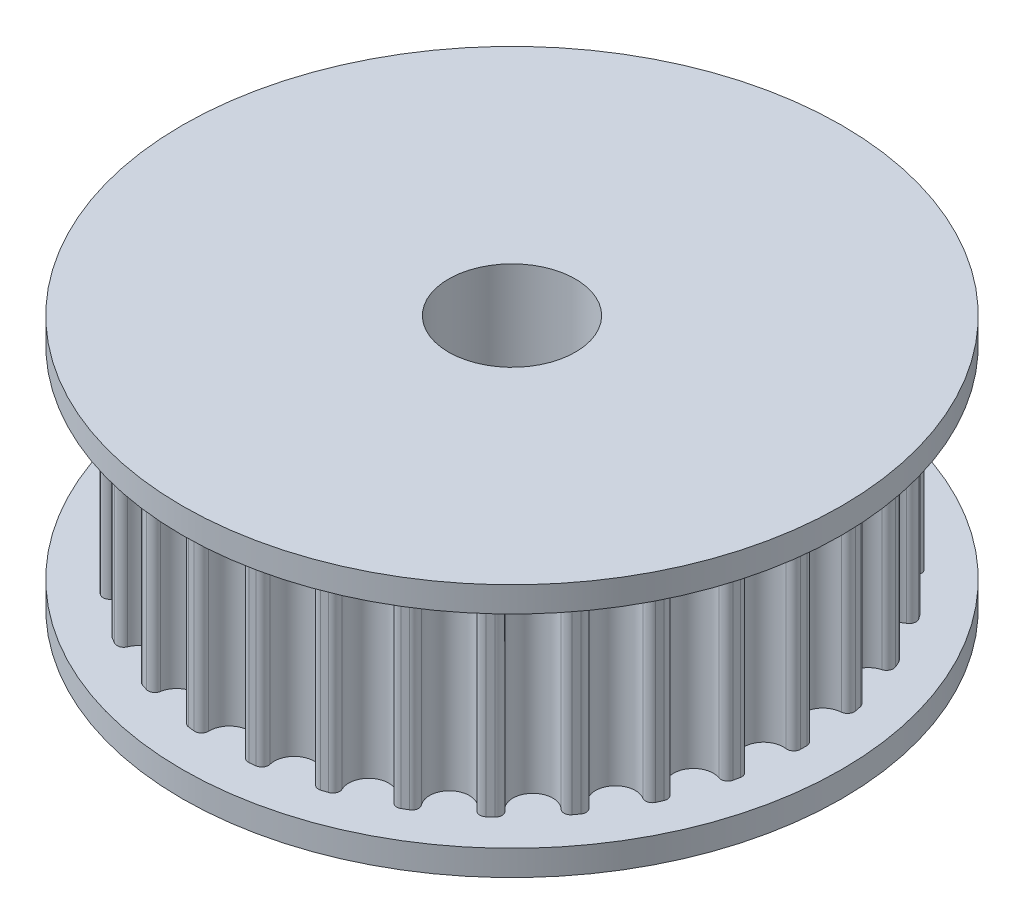
SolidWorks part; units mm, degrees
ref_plane "Front Plane" through (0, 0, 0) normal (0, 0, 1) x (1, 0, 0)
ref_plane "Top Plane" through (0, 0, 0) normal (0, 1, 0) x (1, 0, 0)
ref_plane "Right Plane" through (0, 0, 0) normal (1, 0, 0) x (0, 0, -1)
sketch "Sketch1" plane through (0, 0, 0) normal (0, 1, 0) x (1, 0, 0)
  line L0 (0, 0) -> (23.0032, 0) construction
  line L1 (0, 0) -> (22.8772, 2.4045) construction
  circle A0 centre (0, 0) radius 23.0032 construction
  arc A1 (22.064, 3.9014) -> (22.393, 0.7712) centre (22.1699, 2.3302) ccw
  arc A2 (22.393, 0.7712) -> (23.0019, 0.249) centre (22.4685, 0.2432) cw
  arc A3 (23.0019, 0.249) -> (23.0032, 0) centre (0, 0) cw
  arc A4 (22.064, 3.9014) -> (22.551, 4.5388) centre (22.0281, 4.4336) ccw
  arc A5 (22.551, 4.5388) -> (22.5006, 4.7826) centre (0, 0) ccw
  arc A6 (22.551, -4.5388) -> (22.5006, -4.7826) centre (0, 0) cw
  arc A7 (22.064, -3.9014) -> (22.551, -4.5388) centre (22.0281, -4.4336) cw
  arc A8 (22.393, -0.7712) -> (22.064, -3.9014) centre (22.1699, -2.3302) ccw
  arc A9 (22.393, -0.7712) -> (23.0019, -0.249) centre (22.4685, -0.2432) ccw
  arc A10 (23.0019, -0.249) -> (23.0032, 0) centre (0, 0) ccw
  arc A11 (21.1145, -9.1283) -> (21.0145, -9.3563) centre (0, 0) cw
  arc A12 (20.7707, -8.4035) -> (21.1145, -9.1283) centre (20.6249, -8.9166) cw
  arc A13 (21.7433, -5.4101) -> (20.7707, -8.4035) centre (21.201, -6.8886) ccw
  arc A14 (21.7433, -5.4101) -> (22.4475, -5.0259) centre (21.927, -4.9094) ccw
  arc A15 (22.4475, -5.0259) -> (22.5006, -4.7826) centre (0, 0) ccw
  arc A16 (18.7553, -13.3187) -> (18.61, -13.521) centre (0, 0) cw
  arc A17 (18.5696, -12.5383) -> (18.7553, -13.3187) centre (18.3204, -13.0099) cw
  arc A18 (20.1433, -9.8126) -> (18.5696, -12.5383) centre (19.3055, -11.146) ccw
  arc A19 (20.1433, -9.8126) -> (20.912, -9.5832) centre (20.4271, -9.361) ccw
  arc A20 (20.912, -9.5832) -> (21.0145, -9.3563) centre (0, 0) ccw
  arc A21 (15.5763, -16.9271) -> (15.3922, -17.0947) centre (0, 0) cw
  arc A22 (15.557, -16.1252) -> (15.5763, -16.9271) centre (15.2151, -16.5346) cw
  arc A23 (17.663, -13.7862) -> (15.557, -16.1252) centre (16.5662, -14.9163) ccw
  arc A24 (17.663, -13.7862) -> (18.4626, -13.7216) centre (18.0345, -13.4034) ccw
  arc A25 (18.4626, -13.7216) -> (18.61, -13.521) centre (0, 0) ccw
  arc A26 (11.7166, -19.7957) -> (11.5016, -19.9214) centre (0, 0) cw
  arc A27 (11.8644, -19.0073) -> (11.7166, -19.7957) centre (11.4449, -19.3367) cw
  arc A28 (14.4107, -17.1573) -> (11.8644, -19.0073) centre (13.1029, -18.0346) ccw
  arc A29 (14.4107, -17.1573) -> (15.2062, -17.2603) centre (14.8536, -16.8601) ccw
  arc A30 (15.2062, -17.2603) -> (15.3922, -17.0947) centre (0, 0) ccw
  arc A31 (7.3448, -21.7992) -> (7.1084, -21.8774) centre (0, 0) cw
  arc A32 (7.6533, -21.0587) -> (7.3448, -21.7992) centre (7.1745, -21.2937) cw
  arc A33 (10.5286, -19.7785) -> (7.6533, -21.0587) centre (9.067, -20.3648) ccw
  arc A34 (10.5286, -19.7785) -> (11.2853, -20.0447) centre (11.0236, -19.5799) ccw
  arc A35 (11.2853, -20.0447) -> (11.5016, -19.9214) centre (0, 0) ccw
  arc A36 (2.652, -22.8499) -> (2.4045, -22.8772) centre (0, 0) cw
  arc A37 (3.1077, -22.1897) -> (2.652, -22.8499) centre (2.5905, -22.32) cw
  arc A38 (6.1863, -21.5353) -> (3.1077, -22.1897) centre (4.6348, -21.8049) ccw
  arc A39 (6.1863, -21.5353) -> (6.8712, -21.953) centre (6.7119, -21.444) ccw
  arc A40 (6.8712, -21.953) -> (7.1084, -21.8774) centre (0, 0) ccw
  arc A41 (-2.1567, -22.9019) -> (-2.4045, -22.8772) centre (0, 0) cw
  arc A42 (-1.5737, -22.3509) -> (-2.1567, -22.9019) centre (-2.1067, -22.3709) cw
  arc A43 (1.5737, -22.3509) -> (-1.5737, -22.3509) centre (0, -22.292) ccw
  arc A44 (1.5737, -22.3509) -> (2.1567, -22.9019) centre (2.1067, -22.3709) ccw
  arc A45 (2.1567, -22.9019) -> (2.4045, -22.8772) centre (0, 0) ccw
  arc A46 (-6.8712, -21.953) -> (-7.1084, -21.8774) centre (0, 0) cw
  arc A47 (-6.1863, -21.5353) -> (-6.8712, -21.953) centre (-6.7119, -21.444) cw
  arc A48 (-3.1077, -22.1897) -> (-6.1863, -21.5353) centre (-4.6348, -21.8049) ccw
  arc A49 (-3.1077, -22.1897) -> (-2.652, -22.8499) centre (-2.5905, -22.32) ccw
  arc A50 (-2.652, -22.8499) -> (-2.4045, -22.8772) centre (0, 0) ccw
  arc A51 (-11.2853, -20.0447) -> (-11.5016, -19.9214) centre (0, 0) cw
  arc A52 (-10.5286, -19.7785) -> (-11.2853, -20.0447) centre (-11.0236, -19.5799) cw
  arc A53 (-7.6533, -21.0587) -> (-10.5286, -19.7785) centre (-9.067, -20.3648) ccw
  arc A54 (-7.6533, -21.0587) -> (-7.3448, -21.7992) centre (-7.1745, -21.2937) ccw
  arc A55 (-7.3448, -21.7992) -> (-7.1084, -21.8774) centre (0, 0) ccw
  arc A56 (-15.2062, -17.2603) -> (-15.3922, -17.0947) centre (0, 0) cw
  arc A57 (-14.4107, -17.1573) -> (-15.2062, -17.2603) centre (-14.8536, -16.8601) cw
  arc A58 (-11.8644, -19.0073) -> (-14.4107, -17.1573) centre (-13.1029, -18.0346) ccw
  arc A59 (-11.8644, -19.0073) -> (-11.7166, -19.7957) centre (-11.4449, -19.3367) ccw
  arc A60 (-11.7166, -19.7957) -> (-11.5016, -19.9214) centre (0, 0) ccw
  arc A61 (-18.4626, -13.7216) -> (-18.61, -13.521) centre (0, 0) cw
  arc A62 (-17.663, -13.7862) -> (-18.4626, -13.7216) centre (-18.0345, -13.4034) cw
  arc A63 (-15.557, -16.1252) -> (-17.663, -13.7862) centre (-16.5662, -14.9163) ccw
  arc A64 (-15.557, -16.1252) -> (-15.5763, -16.9271) centre (-15.2151, -16.5346) ccw
  arc A65 (-15.5763, -16.9271) -> (-15.3922, -17.0947) centre (0, 0) ccw
  arc A66 (-20.912, -9.5832) -> (-21.0145, -9.3563) centre (0, 0) cw
  arc A67 (-20.1433, -9.8126) -> (-20.912, -9.5832) centre (-20.4271, -9.361) cw
  arc A68 (-18.5696, -12.5383) -> (-20.1433, -9.8126) centre (-19.3055, -11.146) ccw
  arc A69 (-18.5696, -12.5383) -> (-18.7553, -13.3187) centre (-18.3204, -13.0099) ccw
  arc A70 (-18.7553, -13.3187) -> (-18.61, -13.521) centre (0, 0) ccw
  arc A71 (-22.4475, -5.0259) -> (-22.5006, -4.7826) centre (0, 0) cw
  arc A72 (-21.7433, -5.4101) -> (-22.4475, -5.0259) centre (-21.927, -4.9094) cw
  arc A73 (-20.7707, -8.4035) -> (-21.7433, -5.4101) centre (-21.201, -6.8886) ccw
  arc A74 (-20.7707, -8.4035) -> (-21.1145, -9.1283) centre (-20.6249, -8.9166) ccw
  arc A75 (-21.1145, -9.1283) -> (-21.0145, -9.3563) centre (0, 0) ccw
  arc A77 (-23.0019, -0.249) -> (-23.0032, 0) centre (0, 0) cw
  arc A78 (-22.393, -0.7712) -> (-23.0019, -0.249) centre (-22.4685, -0.2432) cw
  arc A79 (-22.064, -3.9014) -> (-22.393, -0.7712) centre (-22.1699, -2.3302) ccw
  arc A80 (-22.064, -3.9014) -> (-22.551, -4.5388) centre (-22.0281, -4.4336) ccw
  arc A81 (-22.551, -4.5388) -> (-22.5006, -4.7826) centre (0, 0) ccw
  arc A82 (-22.551, 4.5388) -> (-22.5006, 4.7826) centre (0, 0) cw
  arc A83 (-22.064, 3.9014) -> (-22.551, 4.5388) centre (-22.0281, 4.4336) cw
  arc A84 (-22.393, 0.7712) -> (-22.064, 3.9014) centre (-22.1699, 2.3302) ccw
  arc A85 (-22.393, 0.7712) -> (-23.0019, 0.249) centre (-22.4685, 0.2432) ccw
  arc A86 (-23.0019, 0.249) -> (-23.0032, 0) centre (0, 0) ccw
  arc A87 (-21.1145, 9.1283) -> (-21.0145, 9.3563) centre (0, 0) cw
  arc A88 (-20.7707, 8.4035) -> (-21.1145, 9.1283) centre (-20.6249, 8.9166) cw
  arc A89 (-21.7433, 5.4101) -> (-20.7707, 8.4035) centre (-21.201, 6.8886) ccw
  arc A90 (-21.7433, 5.4101) -> (-22.4475, 5.0259) centre (-21.927, 4.9094) ccw
  arc A91 (-22.4475, 5.0259) -> (-22.5006, 4.7826) centre (0, 0) ccw
  arc A92 (-18.7553, 13.3187) -> (-18.61, 13.521) centre (0, 0) cw
  arc A93 (-18.5696, 12.5383) -> (-18.7553, 13.3187) centre (-18.3204, 13.0099) cw
  arc A94 (-20.1433, 9.8126) -> (-18.5696, 12.5383) centre (-19.3055, 11.146) ccw
  arc A95 (-20.1433, 9.8126) -> (-20.912, 9.5832) centre (-20.4271, 9.361) ccw
  arc A96 (-20.912, 9.5832) -> (-21.0145, 9.3563) centre (0, 0) ccw
  arc A97 (-15.5763, 16.9271) -> (-15.3922, 17.0947) centre (0, 0) cw
  arc A98 (-15.557, 16.1252) -> (-15.5763, 16.9271) centre (-15.2151, 16.5346) cw
  arc A99 (-17.663, 13.7862) -> (-15.557, 16.1252) centre (-16.5662, 14.9163) ccw
  arc A100 (-17.663, 13.7862) -> (-18.4626, 13.7216) centre (-18.0345, 13.4034) ccw
  arc A101 (-18.4626, 13.7216) -> (-18.61, 13.521) centre (0, 0) ccw
  arc A102 (-11.7166, 19.7957) -> (-11.5016, 19.9214) centre (0, 0) cw
  arc A103 (-11.8644, 19.0073) -> (-11.7166, 19.7957) centre (-11.4449, 19.3367) cw
  arc A104 (-14.4107, 17.1573) -> (-11.8644, 19.0073) centre (-13.1029, 18.0346) ccw
  arc A105 (-14.4107, 17.1573) -> (-15.2062, 17.2603) centre (-14.8536, 16.8601) ccw
  arc A106 (-15.2062, 17.2603) -> (-15.3922, 17.0947) centre (0, 0) ccw
  arc A107 (-7.3448, 21.7992) -> (-7.1084, 21.8774) centre (0, 0) cw
  arc A108 (-7.6533, 21.0587) -> (-7.3448, 21.7992) centre (-7.1745, 21.2937) cw
  arc A109 (-10.5286, 19.7785) -> (-7.6533, 21.0587) centre (-9.067, 20.3648) ccw
  arc A110 (-10.5286, 19.7785) -> (-11.2853, 20.0447) centre (-11.0236, 19.5799) ccw
  arc A111 (-11.2853, 20.0447) -> (-11.5016, 19.9214) centre (0, 0) ccw
  arc A112 (-2.652, 22.8499) -> (-2.4045, 22.8772) centre (0, 0) cw
  arc A113 (-3.1077, 22.1897) -> (-2.652, 22.8499) centre (-2.5905, 22.32) cw
  arc A114 (-6.1863, 21.5353) -> (-3.1077, 22.1897) centre (-4.6348, 21.8049) ccw
  arc A115 (-6.1863, 21.5353) -> (-6.8712, 21.953) centre (-6.7119, 21.444) ccw
  arc A116 (-6.8712, 21.953) -> (-7.1084, 21.8774) centre (0, 0) ccw
  arc A117 (2.1567, 22.9019) -> (2.4045, 22.8772) centre (0, 0) cw
  arc A118 (1.5737, 22.3509) -> (2.1567, 22.9019) centre (2.1067, 22.3709) cw
  arc A119 (-1.5737, 22.3509) -> (1.5737, 22.3509) centre (0, 22.292) ccw
  arc A120 (-1.5737, 22.3509) -> (-2.1567, 22.9019) centre (-2.1067, 22.3709) ccw
  arc A121 (-2.1567, 22.9019) -> (-2.4045, 22.8772) centre (0, 0) ccw
  arc A122 (6.8712, 21.953) -> (7.1084, 21.8774) centre (0, 0) cw
  arc A123 (6.1863, 21.5353) -> (6.8712, 21.953) centre (6.7119, 21.444) cw
  arc A124 (3.1077, 22.1897) -> (6.1863, 21.5353) centre (4.6348, 21.8049) ccw
  arc A125 (3.1077, 22.1897) -> (2.652, 22.8499) centre (2.5905, 22.32) ccw
  arc A126 (2.652, 22.8499) -> (2.4045, 22.8772) centre (0, 0) ccw
  arc A127 (11.2853, 20.0447) -> (11.5016, 19.9214) centre (0, 0) cw
  arc A128 (10.5286, 19.7785) -> (11.2853, 20.0447) centre (11.0236, 19.5799) cw
  arc A129 (7.6533, 21.0587) -> (10.5286, 19.7785) centre (9.067, 20.3648) ccw
  arc A130 (7.6533, 21.0587) -> (7.3448, 21.7992) centre (7.1745, 21.2937) ccw
  arc A131 (7.3448, 21.7992) -> (7.1084, 21.8774) centre (0, 0) ccw
  arc A132 (15.2062, 17.2603) -> (15.3922, 17.0947) centre (0, 0) cw
  arc A133 (14.4107, 17.1573) -> (15.2062, 17.2603) centre (14.8536, 16.8601) cw
  arc A134 (11.8644, 19.0073) -> (14.4107, 17.1573) centre (13.1029, 18.0346) ccw
  arc A135 (11.8644, 19.0073) -> (11.7166, 19.7957) centre (11.4449, 19.3367) ccw
  arc A136 (11.7166, 19.7957) -> (11.5016, 19.9214) centre (0, 0) ccw
  arc A137 (18.4626, 13.7216) -> (18.61, 13.521) centre (0, 0) cw
  arc A138 (17.663, 13.7862) -> (18.4626, 13.7216) centre (18.0345, 13.4034) cw
  arc A139 (15.557, 16.1252) -> (17.663, 13.7862) centre (16.5662, 14.9163) ccw
  arc A140 (15.557, 16.1252) -> (15.5763, 16.9271) centre (15.2151, 16.5346) ccw
  arc A141 (15.5763, 16.9271) -> (15.3922, 17.0947) centre (0, 0) ccw
  arc A142 (20.912, 9.5832) -> (21.0145, 9.3563) centre (0, 0) cw
  arc A143 (20.1433, 9.8126) -> (20.912, 9.5832) centre (20.4271, 9.361) cw
  arc A144 (18.5696, 12.5383) -> (20.1433, 9.8126) centre (19.3055, 11.146) ccw
  arc A145 (18.5696, 12.5383) -> (18.7553, 13.3187) centre (18.3204, 13.0099) ccw
  arc A146 (18.7553, 13.3187) -> (18.61, 13.521) centre (0, 0) ccw
  arc A147 (22.4475, 5.0259) -> (22.5006, 4.7826) centre (0, 0) cw
  arc A148 (21.7433, 5.4101) -> (22.4475, 5.0259) centre (21.927, 4.9094) cw
  arc A149 (20.7707, 8.4035) -> (21.7433, 5.4101) centre (21.201, 6.8886) ccw
  arc A150 (20.7707, 8.4035) -> (21.1145, 9.1283) centre (20.6249, 8.9166) ccw
  arc A151 (21.1145, 9.1283) -> (21.0145, 9.3563) centre (0, 0) ccw
  circle A152 centre (0, 0) radius 5
  point P23 (20.6038, 2.1655)
  point P44 (0, 0)
  dimension "D1" = 46.0065
  dimension "D3" = 1.5748
  dimension "D4" = 0.5334
  dimension "D7" = 10
  dimension "D2" = 6
  dimension "D5" = 2.286
  dimension "D6" = 30
extrude "Boss-Extrude1" add sketch "Sketch1" along normal mid plane 16
sketch "Sketch2" plane through (0, 8, 0) normal (0, 1, 0) x (1, 0, 0)
  circle A3 centre (0, 0) radius 26
  circle A4 centre (0, 0) radius 5 construction
  circle A5 centre (0, 0) radius 5
  dimension "D2" = 52
extrude "Boss-Extrude3" add sketch "Sketch2" along normal blind 2
mirror "Mirror1" about plane through (0, 0, 0) normal (0, 1, 0) of "Boss-Extrude3"
sketch "BeltOuterFace" plane through (0, -8, 0) normal (0, 1, 0) x (1, 0, 0)
  circle A0 centre (0, 0) radius 24.7432 construction
  dimension "D1" = 49.4865
equation "\"T\"= 30"
equation "\"P\"= 5mm"
equation "\"TanD\"= \"PD\" - \"BeltWidth\""
equation "\"Angle\"= 360 / \"T\""
equation "\"D1@Sketch1\"=\"TanD\""
equation "\"D2@Sketch1\"=\"Angle\"/2"
equation "\"D6@Sketch1\"=\"T\""
equation "\"W\"= 16mm"
equation "\"D1@Boss-Extrude1\"=\"W\""
equation "\"TolRatio\"= 32 / 33"
equation "\"BeltWidth\"= 1.74mm"
equation "\"PD\"= \"T\" * \"P\" / PI"
equation "\"D1@BeltOuterFace\"=\"PD\" + \"BeltWidth\""
